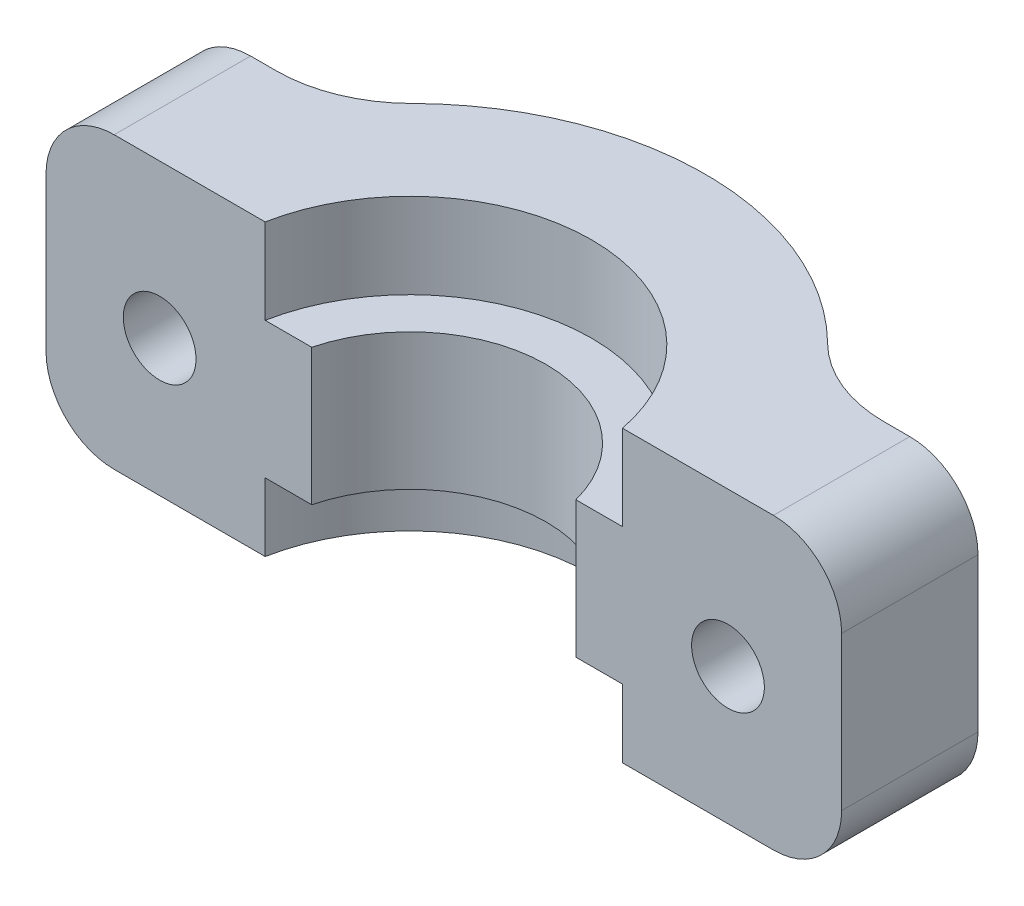
SolidWorks part; units mm, degrees
ref_plane "Front" through (0, 0, 0) normal (0, 0, 1) x (1, 0, 0)
ref_plane "Top" through (0, 0, 0) normal (0, 1, 0) x (1, 0, 0)
ref_plane "Right" through (0, 0, 0) normal (1, 0, 0) x (0, 0, -1)
sketch "Sketch1" plane through (0, 0, 0) normal (0, 1, 0) x (1, 0, 0)
  line L0 (0, 0) -> (44, 0) construction
  line L1 (17.5, 0) -> (17.5, 22.5) construction
  circle A0 centre (17.5, 22.5) radius 6
  dimension "D1" = 44
  dimension "D2" = 12
  dimension "D3" = 22.5
  dimension "D4" = 17.5
sketch "Sketch2" plane through (0, 0, 0) normal (0, 1, 0) x (1, 0, 0)
  line L0 (0, 0) -> (44, 0) construction
  line L1 (0, 0) -> (44, 0)
  line L2 (0, 0) -> (0, 22.5)
  line L3 (0, 22.5) -> (11.5, 22.5)
  line L4 (23.5, 22.5) -> (44, 22.5)
  line L5 (44, 22.5) -> (44, 0)
  circle A0 centre (17.5, 22.5) radius 6 construction
  arc A1 (11.5, 22.5) -> (23.5, 22.5) centre (17.5, 22.5) ccw
extrude "Boss-Extrude1" add sketch "Sketch2" along normal blind 22
sketch "Sketch7" plane through (0, 22, 0) normal (0, -1, 0) x (1, 0, 0)
  line L0 (0, -22.5) -> (0, 0) construction
  line L1 (44, -38.3255) -> (0, -38.3255)
  line L2 (44, -38.3255) -> (44, -9)
  line L3 (44, -9) -> (0, -9)
  line L4 (0, -38.3255) -> (0, -9)
  line L5 (0, 0) -> (44, 0) construction
  line L6 (44, 0) -> (44, -22.5) construction
  dimension "D1" = 9
sketch "Sketch9" plane through (0, 0, 0) normal (0, -1, 0) x (1, 0, 0)
  line L0 (23.5, -22.5) -> (23.5, -24) construction
  line L1 (11.5, -22.5) -> (11.5, -24) construction
  line L2 (11.5, -24) -> (23.5, -24) construction
  line L3 (11.6905, -24) -> (0, -24)
  line L4 (0, -24) -> (0, -30)
  line L5 (0, -30) -> (6.8816, -30)
  line L6 (23.3095, -24) -> (35, -24)
  line L7 (35, -24) -> (35, -30)
  line L8 (35, -30) -> (28.1184, -30)
  arc A0 (23.3095, -24) -> (11.6905, -24) centre (17.5, -22.5) cw
  circle A1 centre (17.5, -22.5) radius 6 construction
  circle A2 centre (17.5, -22.5) radius 13 construction
  arc A3 (28.1184, -30) -> (6.8816, -30) centre (17.5, -22.5) cw
  dimension "D2" = 6
  dimension "D3" = 7
  dimension "D1" = 1.5
extrude "Boss-Extrude2" add sketch "Sketch9" against normal up to surface (22 mm away) separate body up to face at (20.5, 22, -14)
sketch "Sketch5" plane through (0, 0, 0) normal (0, -1, 0) x (1, 0, 0)
  circle A0 centre (17.5, -22.5) radius 8
  dimension "D1" = 16
extrude "Cut-Extrude5" cut sketch "Sketch5" against normal blind 3
sketch "Sketch6" plane through (0, 22, 0) normal (0, 1, 0) x (1, 0, 0)
  circle A0 centre (17.5, 22.5) radius 8
  dimension "D1" = 16
extrude "Cut-Extrude6" cut sketch "Sketch6" against normal offset from surface (13 mm away) 6 up to face at (17.5, 3, -19)
sketch "Sketch8" plane through (0, 0, -22.5) normal (0, 0, -1) x (-1, 0, 0)
  line L0 (-5, 6) -> (0, 6) construction
  line L2 (-17.5, 22) -> (-17.5, 0) construction
  line L3 (-9.5, 22) -> (-25.5, 22) construction
  line L8 (-11.5, 0) -> (-23.5, 0) construction
  line L9 (-5, 6) -> (-11.5, 6) construction
  line L10 (-11.5, 9) -> (-11.5, 3) construction
  line L11 (0, 22) -> (0, 0) construction
  circle A0 centre (-5, 6) radius 2.55
  circle A1 centre (-30, 6) radius 2.55
  dimension "D1" = 5.1
  dimension "D2" = 5
extrude "Cut-Extrude7" cut sketch "Sketch8" against normal blind 7
extrude "Cut-Extrude8" cut sketch "Sketch7" along normal blind 9.25
fillet "Fillet1" radius 6 2 edges at (28.1184, 6.375, -30) (6.8816, 6.375, -30)
sketch "Sketch10" plane through (0, 0, -30) normal (0, 0, -1) x (-1, 0, 0)
  circle A0 centre (-5, 6) radius 3.25
  circle A1 centre (-30, 6) radius 3.25
  dimension "D1" = 6.5
extrude "Cut-Extrude9" cut sketch "Sketch10" along normal through all
sketch "Sketch11" plane through (0, 0, -30) normal (0, 0, -1) x (-1, 0, 0)
  circle A0 centre (-5, 6) radius 1.6
  circle A1 centre (-30, 6) radius 1.6
  dimension "D1" = 3.2
extrude "Cut-Extrude10" cut sketch "Sketch11" against normal up to next (6 mm away)
sketch "Sketch12" [suppressed] plane through (0, 0, 0) normal (0, -1, 0) x (1, 0, 0)
  line L1 (0, 0) -> (44, 0)
  line L2 (0, 0) -> (0, -7.5)
  line L3 (0, -7.5) -> (44, -7.5)
  line L4 (44, 0) -> (44, -7.5)
  line L5 (44, 0) -> (44, -22.5) construction
  dimension "D1" = 7.5
extrude "Boss-Extrude3" [suppressed] add sketch "Sketch12" along normal blind 9.25
sketch "Sketch13" [suppressed] plane through (0, 0, -9) normal (0, 0, -1) x (-1, 0, 0)
  line L4 (0, 22) -> (-44, 22)
  line L5 (-44, 22) -> (-44, 12.75)
  line L6 (-44, 12.75) -> (0, 12.75)
  line L7 (0, 12.75) -> (0, 22)
  line L8 (0, 22) -> (-44, 22)
  line L9 (-44, 22) -> (-44, 12.75)
  line L10 (-44, 12.75) -> (0, 12.75)
  line L11 (0, 12.75) -> (0, 22)
  dimension "D1" = 0
extrude "Cut-Extrude11" [suppressed] cut sketch "Sketch13" against normal through all
sketch "Sketch3" [suppressed] plane through (0, 0, 0) normal (0, 0, 1) x (1, 0, 0)
  line L0 (5, 8.75) -> (5, -5.25) construction
  line L1 (5, -5.25) -> (5, -9.25) construction
  line L2 (44, 12.75) -> (0, 12.75) construction
  line L3 (5, 8.75) -> (5, 12.75) construction
  line L5 (22, -9.25) -> (22, 12.75) construction
  line L7 (44, -9.25) -> (0, -9.25) construction
  circle A0 centre (5, 8.75) radius 2.55
  circle A1 centre (5, -5.25) radius 2.55
  circle A2 centre (39, -5.25) radius 2.55
  circle A3 centre (39, 8.75) radius 2.55
  dimension "D1" = 5.1
  dimension "D2" = 14
  dimension "D3" = 34
extrude "holes" [suppressed] cut sketch "Sketch3" against normal blind 7
fillet "Fillet3" radius 3 4 edges at (0, 0, -27) (0, 12.75, -27) (35, 0, -27) (35, 12.75, -27)
fillet "Fillet4" [suppressed] radius 3
fillet "Fillet5" [suppressed] radius 3
delete or keep bodies "Body-Delete/Keep 1" type delete bodies bodies 109
delete or keep bodies "Body-Delete/Keep 2" [suppressed] type delete bodies bodies 114
other "Move Face1" [suppressed] parameters "D1"=0.5
